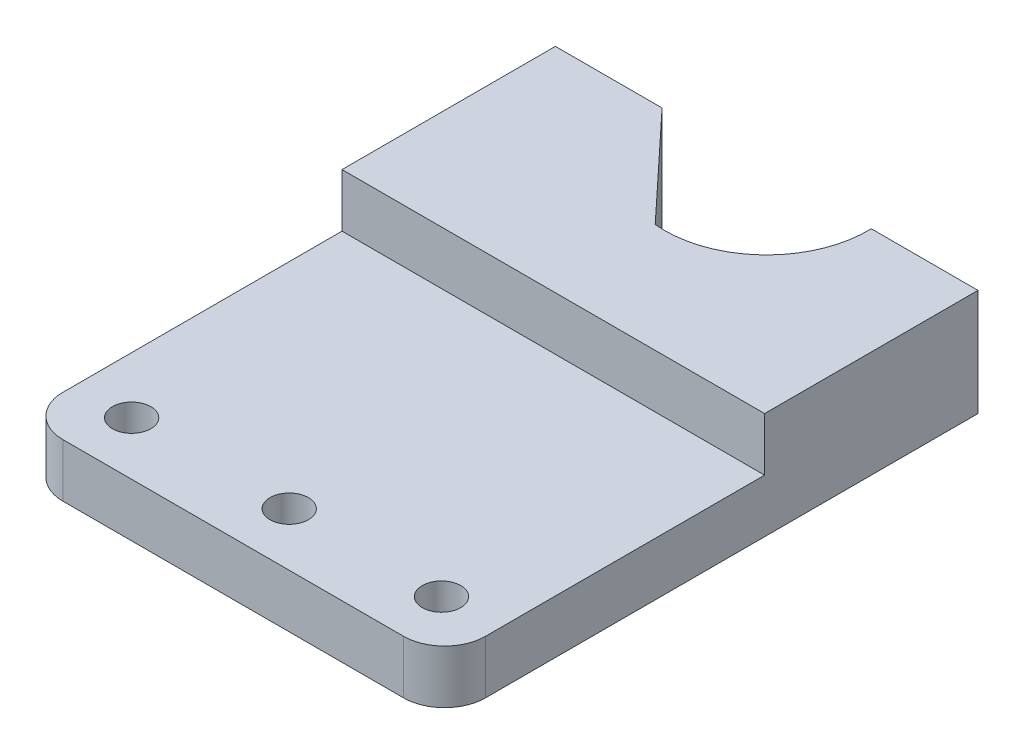
SolidWorks part; units mm, degrees
ref_plane "Front Plane" through (0, 0, 0) normal (0, 0, 1) x (1, 0, 0)
ref_plane "Top Plane" through (0, 0, 0) normal (0, 1, 0) x (1, 0, 0)
ref_plane "Right Plane" through (0, 0, 0) normal (1, 0, 0) x (0, 0, -1)
sketch "Sketch1" plane through (0, 0, 0) normal (0, 1, 0) x (1, 0, 0)
  line L0 (-291.7555, 191.3965) -> (-280.1512, 178.9731)
  line L1 (-266.8509, 191.3965) -> (-254.1509, 191.3965)
  line L2 (-291.7555, 191.3965) -> (-304.4555, 191.3965)
  line L6 (-280.1512, 178.9731) -> (-266.8509, 191.3965) construction
  line L11 (-304.4555, 191.3965) -> (-304.4555, 127.8965)
  line L12 (-304.4555, 127.8965) -> (-254.1509, 127.8965)
  line L13 (-254.1509, 127.8965) -> (-254.1509, 191.3965)
  line L17 (-297.7461, 134.2465) -> (-260.8603, 134.2465) construction
  line L18 (-297.7461, 134.2465) -> (-304.4555, 134.2465) construction
  line L19 (-260.8603, 134.2465) -> (-254.1509, 134.2465) construction
  arc A0 (-280.1512, 178.9731) -> (-266.8509, 191.3965) centre (-278.9448, 191.0128) ccw
  circle A1 centre (-297.7461, 134.2465) radius 2.286
  circle A2 centre (-278.9904, 134.2465) radius 2.286
  circle A3 centre (-260.8603, 134.2465) radius 2.286
  dimension "D2" = 18.2
  dimension "D5" = 12.1
  dimension "D7" = 4.572
  dimension "D1" = 17
  dimension "D3" = 6.35
  dimension "D4" = 90
  dimension "D6" = 12.7
  dimension "D8" = 63.5
extrude "Boss-Extrude1" add sketch "Sketch1" along normal blind 12.7
sketch "Sketch5" plane through (0, 0, -191.3965) normal (0, 0, -1) x (-1, 0, 0)
  line L0 (254.1509, 6.35) -> (304.4555, 6.35) construction
  line L1 (254.1509, 12.7) -> (254.1509, 0) construction
  line L2 (304.4555, 12.7) -> (304.4555, 0) construction
  line L3 (260.5009, 12.7) -> (260.5009, 0) construction
  line L4 (254.1509, 12.7) -> (266.8509, 12.7) construction
  line L5 (254.1509, 0) -> (266.8509, 0) construction
  line L6 (298.1055, 12.7) -> (298.1055, 0) construction
  line L7 (291.7555, 12.7) -> (304.4555, 12.7) construction
  line L8 (291.7555, 0) -> (304.4555, 0) construction
  circle A0 centre (260.5009, 6.35) radius 2.286
  circle A1 centre (298.1055, 6.35) radius 2.286
  dimension "D1" = 4.572
extrude "Cut-Extrude3" cut sketch "Sketch5" against normal blind 12.7
fillet "Fillet1" radius 4.87 1 edges at (-304.4555, 6.35, -127.8965)
fillet "Fillet2" radius 4.87 1 edges at (-254.1509, 6.35, -127.8965)
sketch "Sketch7" plane through (0, 12.7, 0) normal (0, 1, 0) x (1, 0, 0)
  line L0 (-254.1509, 165.9965) -> (-304.4555, 165.9965)
  line L1 (-254.1509, 127.8965) -> (-254.1509, 191.3965) construction
  line L2 (-304.4555, 165.9965) -> (-304.4555, 127.8965)
  line L3 (-304.4555, 127.8965) -> (-254.1509, 127.8965)
  line L4 (-254.1509, 127.8965) -> (-254.1509, 165.9965)
  line L5 (-304.4555, 191.3965) -> (-304.4555, 127.8965) construction
  line L6 (-266.8509, 191.3965) -> (-254.1509, 191.3965) construction
  dimension "D1" = 25.4
extrude "Cut-Extrude4" cut sketch "Sketch7" against normal blind 6.35
